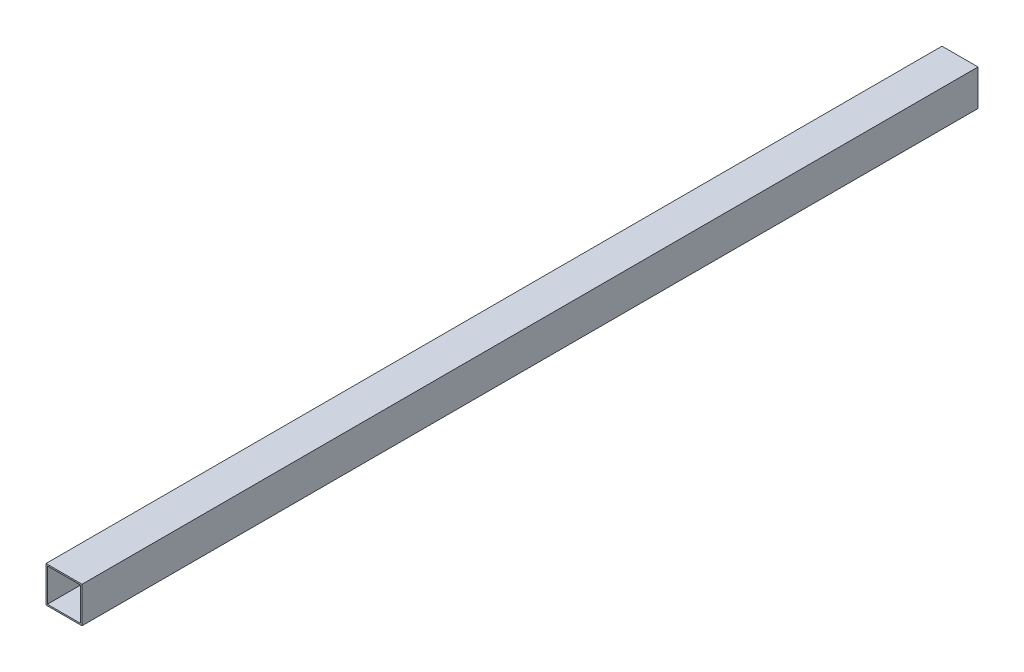
SolidWorks part; units mm, degrees
ref_plane "Front Plane" through (0, 0, 0) normal (0, 0, 1) x (1, 0, 0)
ref_plane "Top Plane" through (0, 0, 0) normal (0, 1, 0) x (1, 0, 0)
ref_plane "Right Plane" through (0, 0, 0) normal (1, 0, 0) x (0, 0, -1)
sketch "Sketch1" plane through (0, 0, 0) normal (0, 0, 1) x (1, 0, 0)
  line L1 (6, 6) -> (-6, 6)
  line L2 (6, 6) -> (6, -6)
  line L3 (6, -6) -> (-6, -6)
  line L4 (-6, 6) -> (-6, -6)
  line L5 (6, 6) -> (-6, -6) construction
  line L6 (6, -6) -> (-6, 6) construction
  line L7 (-6.5, 6.5) -> (6.5, 6.5)
  line L8 (-6.5, 6.5) -> (-6.5, -6.5)
  line L9 (-6.5, -6.5) -> (6.5, -6.5)
  line L10 (6.5, 6.5) -> (6.5, -6.5)
  line L11 (-6.5, 6.5) -> (6.5, -6.5) construction
  line L12 (-6.5, -6.5) -> (6.5, 6.5) construction
  point P1 (0, 0)
  point P6 (0, 0)
  dimension "D1" = 12
  dimension "D2" = 13
  dimension "D3" = 13
  dimension "D4" = 12
extrude "Boss-Extrude1" add sketch "Sketch1" along normal blind 323.5
